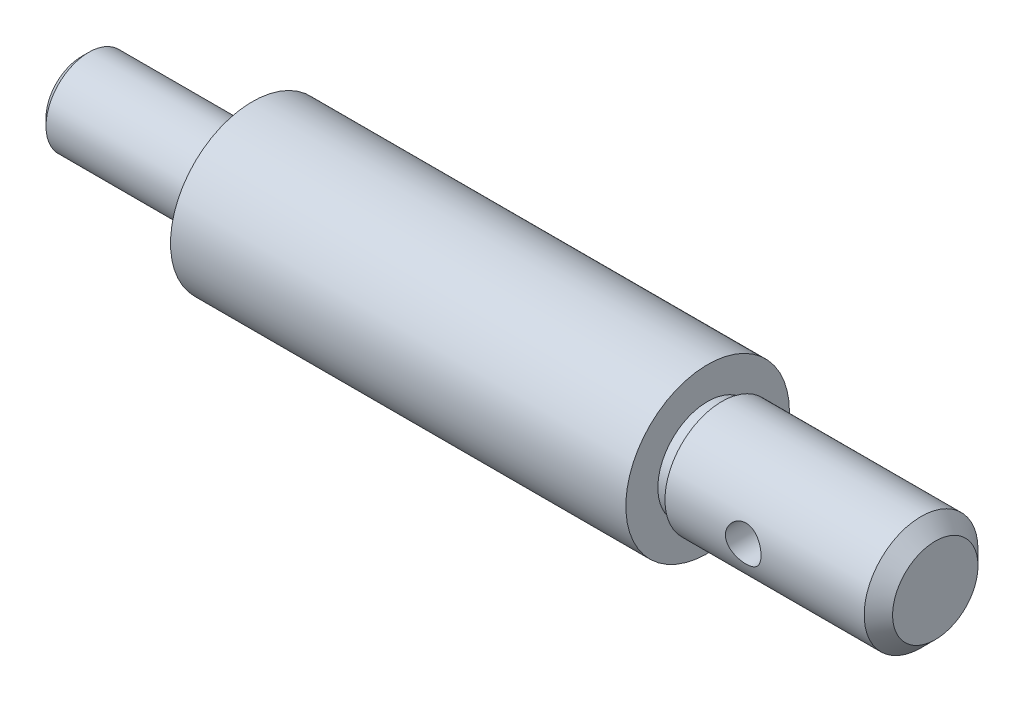
SolidWorks part; units mm, degrees
ref_plane "Front Plane" through (0, 0, 0) normal (0, 0, 1) x (1, 0, 0)
ref_plane "Top Plane" through (0, 0, 0) normal (0, 1, 0) x (1, 0, 0)
ref_plane "Right Plane" through (0, 0, 0) normal (1, 0, 0) x (0, 0, -1)
sketch "Sketch2" plane through (0, 0, 0) normal (0, 0, 1) x (1, 0, 0)
  line L0 (0, 0) -> (-120, 0) construction
  line L1 (0, 0) -> (-30, 0)
  line L2 (0, 0) -> (0, 8)
  line L3 (0, 8) -> (-30, 8)
  line L4 (-30, 7) -> (-30, 8)
  line L6 (-30, 0) -> (-32, 0)
  line L8 (-30, 7) -> (-32, 7)
  line L10 (-32, 0) -> (-96, 0)
  line L11 (-32, 7) -> (-32, 11.5)
  line L12 (-32, 11.5) -> (-96, 11.5)
  line L13 (-96, 5) -> (-96, 11.5)
  line L14 (-96, 0) -> (-98, 0)
  line L16 (-96, 5) -> (-98, 5)
  line L18 (-98, 0) -> (-120, 0)
  line L19 (-98, 5) -> (-98, 6)
  line L20 (-98, 6) -> (-120, 6)
  line L21 (-120, 0) -> (-120, 6)
revolve "Revolve1" add sketch "Sketch2" angle 360 about L0
cosmetic thread "Cosmetic Thread1" parameters "D2"=10.344
sketch "Sketch3" plane through (0, 0, 0) normal (0, 0, 1) x (1, 0, 0)
  line L0 (0, 0) -> (-19, 0) construction
  circle A0 centre (-19, 0) radius 2.5
extrude "Cut-Extrude1" cut sketch "Sketch3" against normal mid plane 20
chamfer "Chamfer1" distance 2 1 edges at (0, 0, -8)
chamfer "Chamfer2" distance 1 1 edges at (-120, 0, -6)
